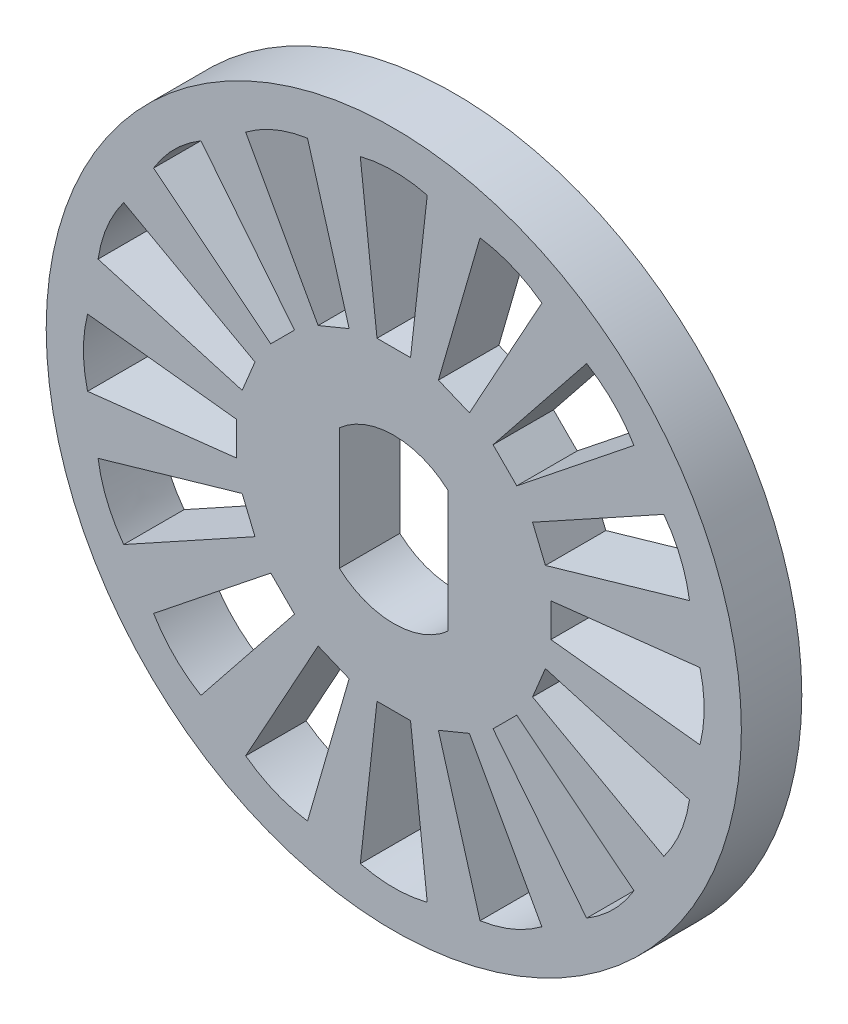
SolidWorks part; units mm, degrees
ref_plane "Front Plane" through (0, 0, 0) normal (0, 0, 1) x (1, 0, 0)
ref_plane "Top Plane" through (0, 0, 0) normal (0, 1, 0) x (1, 0, 0)
ref_plane "Right Plane" through (0, 0, 0) normal (1, 0, 0) x (0, 0, -1)
sketch "Sketch1" plane through (0, 0, 0) normal (0, 0, 1) x (1, 0, 0)
  line L0 (0, 29.3396) -> (0, -28.4316) construction
  line L1 (-34.5346, 0) -> (35.2675, 0) construction
  circle A0 centre (0, 0) radius 11.5
  dimension "D1" = 23
extrude "Boss-Extrude1" add sketch "Sketch1" along normal blind 2
sketch "Sketch2" plane through (0, 0, 2) normal (0, 0, 1) x (1, 0, 0)
  line L0 (0, 12.0457) -> (0, -12.3213) construction
  line L1 (-16.0712, 0) -> (16.7447, 0) construction
  line L2 (1.8, 2.0125) -> (1.8, -2.0125)
  line L3 (-1.8, 2.0125) -> (-1.8, -2.0125)
  arc A0 (-1.8, -2.0125) -> (1.8, -2.0125) centre (0, 0) ccw
  arc A1 (1.8, 2.0125) -> (-1.8, 2.0125) centre (0, 0) ccw
  point P11 (0, 0)
  dimension "D1" = 3.6
  dimension "D2" = 5.4
extrude "Cut-Extrude1" cut sketch "Sketch2" against normal blind 2
sketch "Sketch3" plane through (0, 0, 2) normal (0, 0, 1) x (1, 0, 0)
  line L0 (0, 12.1988) -> (0, -12.3825) construction
  line L1 (-14.8773, 0) -> (14.2345, 0) construction
  line L2 (-0.555, 5.2) -> (0.555, 5.2)
  line L3 (0.555, 5.2) -> (1.1073, 10.1308)
  line L4 (-0.555, 5.2) -> (-1.1073, 10.1308)
  line L6 (2.5027, 4.5918) -> (4.8999, 8.9359)
  line L7 (1.4772, 5.0166) -> (2.5027, 4.5918)
  line L8 (1.4772, 5.0166) -> (2.8539, 9.7834)
  line L9 (4.0694, 3.2845) -> (7.9466, 6.3806)
  line L10 (3.2845, 4.0694) -> (4.0694, 3.2845)
  line L11 (3.2845, 4.0694) -> (6.3806, 7.9466)
  line L12 (5.0166, 1.4772) -> (9.7834, 2.8539)
  line L13 (4.5918, 2.5027) -> (5.0166, 1.4772)
  line L14 (4.5918, 2.5027) -> (8.9359, 4.8999)
  line L15 (5.2, -0.555) -> (10.1308, -1.1073)
  line L16 (5.2, 0.555) -> (5.2, -0.555)
  line L17 (5.2, 0.555) -> (10.1308, 1.1073)
  line L18 (4.5918, -2.5027) -> (8.9359, -4.8999)
  line L19 (5.0166, -1.4772) -> (4.5918, -2.5027)
  line L20 (5.0166, -1.4772) -> (9.7834, -2.8539)
  line L21 (3.2845, -4.0694) -> (6.3806, -7.9466)
  line L22 (4.0694, -3.2845) -> (3.2845, -4.0694)
  line L23 (4.0694, -3.2845) -> (7.9466, -6.3806)
  line L24 (1.4772, -5.0166) -> (2.8539, -9.7834)
  line L25 (2.5027, -4.5918) -> (1.4772, -5.0166)
  line L26 (2.5027, -4.5918) -> (4.8999, -8.9359)
  line L27 (-0.555, -5.2) -> (-1.1073, -10.1308)
  line L28 (0.555, -5.2) -> (-0.555, -5.2)
  line L29 (0.555, -5.2) -> (1.1073, -10.1308)
  line L30 (-2.5027, -4.5918) -> (-4.8999, -8.9359)
  line L31 (-1.4772, -5.0166) -> (-2.5027, -4.5918)
  line L32 (-1.4772, -5.0166) -> (-2.8539, -9.7834)
  line L33 (-4.0694, -3.2845) -> (-7.9466, -6.3806)
  line L34 (-3.2845, -4.0694) -> (-4.0694, -3.2845)
  line L35 (-3.2845, -4.0694) -> (-6.3806, -7.9466)
  line L36 (-5.0166, -1.4772) -> (-9.7834, -2.8539)
  line L37 (-4.5918, -2.5027) -> (-5.0166, -1.4772)
  line L38 (-4.5918, -2.5027) -> (-8.9359, -4.8999)
  line L39 (-5.2, 0.555) -> (-10.1308, 1.1073)
  line L40 (-5.2, -0.555) -> (-5.2, 0.555)
  line L41 (-5.2, -0.555) -> (-10.1308, -1.1073)
  line L42 (-4.5918, 2.5027) -> (-8.9359, 4.8999)
  line L43 (-5.0166, 1.4772) -> (-4.5918, 2.5027)
  line L44 (-5.0166, 1.4772) -> (-9.7834, 2.8539)
  line L45 (-3.2845, 4.0694) -> (-6.3806, 7.9466)
  line L46 (-4.0694, 3.2845) -> (-3.2845, 4.0694)
  line L47 (-4.0694, 3.2845) -> (-7.9466, 6.3806)
  line L48 (-1.4772, 5.0166) -> (-2.8539, 9.7834)
  line L49 (-2.5027, 4.5918) -> (-1.4772, 5.0166)
  line L50 (-2.5027, 4.5918) -> (-4.8999, 8.9359)
  arc A2 (1.8, 2.0125) -> (-1.8, 2.0125) centre (0, 0) ccw construction
  spline S0 degree 2 poles (-1.1073, 10.1308) (0, 10.4071) (1.1073, 10.1308) knots 0 0 0 1 1 1
  spline S1 degree 2 poles (2.8539, 9.7834) (3.9826, 9.6149) (4.8999, 8.9359) knots 0 0 0 1 1 1
  spline S2 degree 2 poles (6.3806, 7.9466) (7.3589, 7.3589) (7.9466, 6.3806) knots 0 0 0 1 1 1
  spline S3 degree 2 poles (8.9359, 4.8999) (9.6149, 3.9826) (9.7834, 2.8539) knots 0 0 0 1 1 1
  spline S4 degree 2 poles (10.1308, 1.1073) (10.4071, 0) (10.1308, -1.1073) knots 0 0 0 1 1 1
  spline S5 degree 2 poles (9.7834, -2.8539) (9.6149, -3.9826) (8.9359, -4.8999) knots 0 0 0 1 1 1
  spline S6 degree 2 poles (7.9466, -6.3806) (7.3589, -7.3589) (6.3806, -7.9466) knots 0 0 0 1 1 1
  spline S7 degree 2 poles (4.8999, -8.9359) (3.9826, -9.6149) (2.8539, -9.7834) knots 0 0 0 1 1 1
  spline S8 degree 2 poles (1.1073, -10.1308) (0, -10.4071) (-1.1073, -10.1308) knots 0 0 0 1 1 1
  spline S9 degree 2 poles (-2.8539, -9.7834) (-3.9826, -9.6149) (-4.8999, -8.9359) knots 0 0 0 1 1 1
  spline S10 degree 2 poles (-6.3806, -7.9466) (-7.3589, -7.3589) (-7.9466, -6.3806) knots 0 0 0 1 1 1
  spline S11 degree 2 poles (-8.9359, -4.8999) (-9.6149, -3.9826) (-9.7834, -2.8539) knots 0 0 0 1 1 1
  spline S12 degree 2 poles (-10.1308, -1.1073) (-10.4071, 0) (-10.1308, 1.1073) knots 0 0 0 1 1 1
  spline S13 degree 2 poles (-9.7834, 2.8539) (-9.6149, 3.9826) (-8.9359, 4.8999) knots 0 0 0 1 1 1
  spline S14 degree 2 poles (-7.9466, 6.3806) (-7.3589, 7.3589) (-6.3806, 7.9466) knots 0 0 0 1 1 1
  spline S15 degree 2 poles (-4.8999, 8.9359) (-3.9826, 9.6149) (-2.8539, 9.7834) knots 0 0 0 1 1 1
  point P5 (0.5279, 5.7)
  point P10 (1.3596, 10.0842)
  point P15 (0, 0)
  point P91 (0, 0)
  point P92 (1.1073, 10.1308)
  point P93 (0.5144, 5.7)
  point P94 (0, 0)
  point P95 (-0.6141, 5.7)
  point P96 (-0.555, 5.2)
  dimension "D2" = 2.5
  dimension "D1" = 16
extrude "Cut-Extrude2" cut sketch "Sketch3" against normal blind 2
